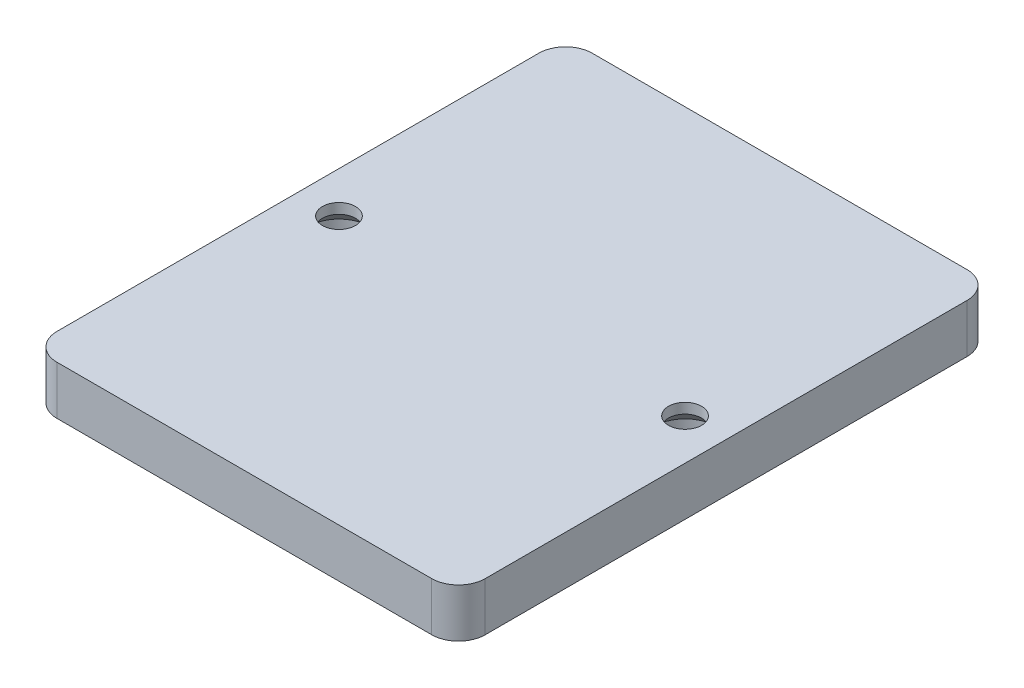
SolidWorks part; units mm, degrees
ref_plane "Front Plane" through (0, 0, 0) normal (0, 0, 1) x (1, 0, 0)
ref_plane "Top Plane" through (0, 0, 0) normal (0, 1, 0) x (1, 0, 0)
ref_plane "Right Plane" through (0, 0, 0) normal (1, 0, 0) x (0, 0, -1)
sketch "Sketch1" plane through (0, 0, 0) normal (0, 1, 0) x (1, 0, 0)
  line L0 (0, 0) -> (0, 27.5) construction
  line L1 (-19.25, -27.5) -> (19.25, -27.5)
  line L2 (-22, -24.75) -> (-22, 24.75)
  line L3 (-19.25, 27.5) -> (19.25, 27.5)
  line L4 (22, -24.75) -> (22, 24.75)
  line L5 (-22, -27.5) -> (22, 27.5) construction
  line L6 (-22, 27.5) -> (22, -27.5) construction
  circle A0 centre (-17.78, 0) radius 1.5
  circle A1 centre (17.78, 0) radius 1.5
  arc A2 (-19.25, -27.5) -> (-22, -24.75) centre (-19.25, -24.75) cw
  arc A3 (19.25, -27.5) -> (22, -24.75) centre (19.25, -24.75) ccw
  arc A4 (19.25, 27.5) -> (22, 24.75) centre (19.25, 24.75) cw
  arc A5 (-22, 24.75) -> (-19.25, 27.5) centre (-19.25, 24.75) cw
  point P0 (0, 0)
  point P10 (0, 0)
  dimension "D3" = 3
  dimension "D5" = 2.75
  dimension "D1" = 44
  dimension "D2" = 55
  dimension "D4" = 35.56
extrude "Boss-Extrude1" add sketch "Sketch1" along normal blind 2.5
hole_wizard "CSK for M3 Flat Head Machine Screw1" positions "Sketch2" profile "Sketch3" countersink size "M3" standard "ANSI Metric"
sketch "Sketch2" plane through (0, 0, 0) normal (0, -1, 0) x (-1, 0, 0)
  point P0 (-17.78, 0)
  point P3 (17.78, 0)
sketch "Sketch3" plane through (17.78, 0, 0) normal (1, 0, 0) x (0, 0, -1)
  line L0 (0, 0) -> (0, 11.0215)
  line L1 (0, 11.0215) -> (1.7, 10)
  line L2 (1.7, 10) -> (1.7, 1.45)
  line L3 (1.7, 1.45) -> (3.15, 0)
  line L5 (3.15, 0) -> (0, 0)
  line L6 (-1.7, 1.45) -> (-3.15, 0) construction
  line L10 (0, 11.0215) -> (-1.7, 10) construction
  line L11 (0, -6.35) -> (0, 107.95) construction
  dimension "Hole Dia." = 3.4
  dimension "Hole Depth" = 10
  dimension "Near C'Sink Dia." = 6.3
  dimension "Near C'Sink Angle" = 90
  dimension "Drill Angle" = 118
sketch "Sketch4" plane through (0, 0, 0) normal (0, -1, 0) x (1, 0, 0)
  line L4 (-22, 24.75) -> (-22, -24.75)
  line L5 (-19.25, -27.5) -> (19.25, -27.5)
  line L6 (22, -24.75) -> (22, 24.75)
  line L7 (19.25, 27.5) -> (-19.25, 27.5)
  line L8 (-22, 24.75) -> (-22, -24.75)
  line L9 (-19.25, -27.5) -> (19.25, -27.5)
  line L10 (22, -24.75) -> (22, 24.75)
  line L11 (19.25, 27.5) -> (-19.25, 27.5)
  circle A0 centre (17.78, 0) radius 3.15 construction
  circle A1 centre (-17.78, 0) radius 3.15 construction
  circle A2 centre (17.78, 0) radius 3.15 construction
  circle A3 centre (-17.78, 0) radius 3.15 construction
  arc A4 (-19.25, 27.5) -> (-22, 24.75) centre (-19.25, 24.75) ccw
  arc A5 (-22, -24.75) -> (-19.25, -27.5) centre (-19.25, -24.75) ccw
  arc A6 (19.25, -27.5) -> (22, -24.75) centre (19.25, -24.75) ccw
  arc A7 (22, 24.75) -> (19.25, 27.5) centre (19.25, 24.75) ccw
  arc A8 (-19.25, 27.5) -> (-22, 24.75) centre (-19.25, 24.75) ccw
  arc A9 (-22, -24.75) -> (-19.25, -27.5) centre (-19.25, -24.75) ccw
  arc A10 (19.25, -27.5) -> (22, -24.75) centre (19.25, -24.75) ccw
  arc A11 (22, 24.75) -> (19.25, 27.5) centre (19.25, 24.75) ccw
  circle A12 centre (-17.78, 0) radius 3.45
  circle A13 centre (17.78, 0) radius 3.45
  dimension "D1" = 0
  dimension "D2" = 0.3
extrude "Boss-Extrude2" add sketch "Sketch4" along normal blind 2.5
